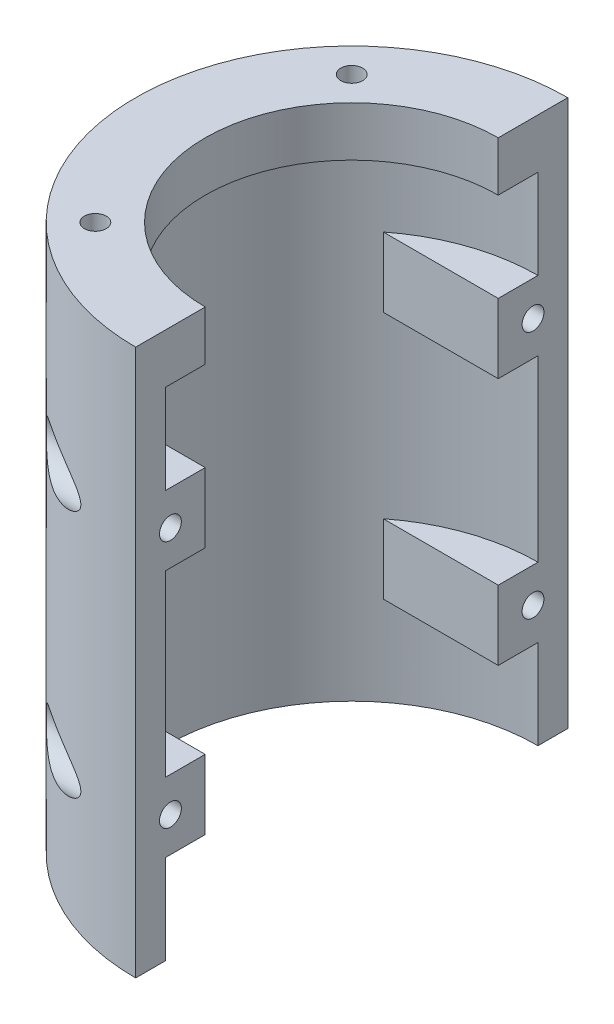
SolidWorks part; units mm, degrees
ref_plane "正面" through (0, 0, 0) normal (0, 0, 1) x (1, 0, 0)
ref_plane "平面" through (0, 0, 0) normal (0, 1, 0) x (1, 0, 0)
ref_plane "右側面" through (0, 0, 0) normal (1, 0, 0) x (0, 0, -1)
sketch "ｽｹｯﾁ1" plane through (0, 0, 0) normal (0, 1, 0) x (1, 0, 0)
  line L0 (0, -21.75) -> (0, -14.75)
  line L1 (0, -14.75) -> (0, 14.75) construction
  line L2 (0, 14.75) -> (0, 21.75)
  arc A0 (0, 21.75) -> (0, -21.75) centre (0, 0) ccw
  arc A1 (0, 14.75) -> (0, -14.75) centre (0, 0) ccw
  dimension "D1" = 14.75
  dimension "D2" = 7
extrude "ﾎﾞｽ - 押し出し1" add sketch "ｽｹｯﾁ1" along normal blind 55
sketch "ｽｹｯﾁ2" plane through (0, 55, 0) normal (0, 1, 0) x (1, 0, 0)
  circle A0 centre (0, 0) radius 14.75
  circle A1 centre (0, 0) radius 18.75
  arc A2 (0, 14.75) -> (0, -14.75) centre (0, 0) ccw construction
  arc A3 (0, 21.75) -> (0, -21.75) centre (0, 0) ccw construction
  dimension "D1" = 3
extrude "ｶｯﾄ - 押し出し1" cut sketch "ｽｹｯﾁ2" against normal through all from offset 5 offset against normal yes
sketch "ｽｹｯﾁ4" plane through (0, 0, 0) normal (1, 0, 0) x (0, 0, -1)
  line L0 (-14.75, 12.5) -> (-21.75, 12.5) construction
  line L1 (-21.75, 41) -> (-21.75, 34)
  line L2 (-18.75, 50) -> (-14.75, 50) construction
  line L3 (21.75, 55) -> (21.75, 0) construction
  line L4 (18.75, 50) -> (18.75, 0) construction
  line L5 (-21.75, 16) -> (-14.75, 16)
  line L6 (-14.75, 16) -> (-14.75, 9)
  line L7 (-14.75, 9) -> (-21.75, 9)
  line L8 (-21.75, 9) -> (-21.75, 16)
  line L9 (-21.75, 50) -> (21.75, 50) construction
  line L10 (0, 25) -> (-21.75, 25) construction
  line L11 (0, 25) -> (21.75, 25) construction
  line L12 (-21.75, 37.5) -> (21.75, 37.5) construction
  line L13 (-21.75, 0) -> (21.75, 0) construction
  line L14 (0, 50) -> (0, 0) construction
  line L15 (-18.25, 50) -> (-18.25, 0) construction
  line L16 (18.75, 50) -> (18.75, 37.5) construction
  line L17 (18.75, 37.5) -> (18.75, 25) construction
  line L18 (-21.75, 55) -> (-21.75, 0) construction
  line L19 (-21.75, 34) -> (-14.75, 34)
  line L20 (-14.75, 34) -> (-14.75, 41)
  line L21 (-14.75, 41) -> (-21.75, 41)
  line L22 (21.75, 9) -> (21.75, 16)
  line L23 (21.75, 16) -> (14.75, 16)
  line L24 (14.75, 16) -> (14.75, 9)
  line L25 (14.75, 9) -> (21.75, 9)
  line L26 (21.75, 34) -> (14.75, 34)
  line L27 (21.75, 41) -> (21.75, 34)
  line L28 (14.75, 41) -> (21.75, 41)
  line L29 (14.75, 34) -> (14.75, 41)
  circle A0 centre (-18.25, 37.5) radius 1.1 construction
  circle A1 centre (18.25, 37.5) radius 1.1 construction
  circle A2 centre (18.25, 12.5) radius 1.1 construction
  circle A3 centre (-18.25, 12.5) radius 1.1 construction
  dimension "D1" = 2.2
  dimension "D2" = 3.5
  dimension "D3" = 7
  dimension "D4" = 7
extrude "ﾎﾞｽ - 押し出し3" add sketch "ｽｹｯﾁ4" against normal up to next
sketch "ｽｹｯﾁ3" plane through (0, 0, 0) normal (1, 0, 0) x (0, 0, -1)
  line L0 (-21.75, 50) -> (21.75, 50) construction
  line L1 (0, 25) -> (-21.75, 25) construction
  line L2 (0, 25) -> (21.75, 25) construction
  line L3 (-21.75, 55) -> (-21.75, 0) construction
  line L4 (-21.75, 37.5) -> (21.75, 37.5) construction
  line L5 (21.75, 55) -> (21.75, 0) construction
  line L6 (-21.75, 0) -> (21.75, 0) construction
  line L7 (0, 50) -> (0, 0) construction
  line L8 (14.75, 50) -> (18.75, 50) construction
  line L9 (-18.25, 50) -> (-18.25, 0) construction
  line L10 (18.75, 50) -> (18.75, 37.5) construction
  line L11 (18.75, 37.5) -> (18.75, 25) construction
  line L12 (18.75, 50) -> (18.75, 41) construction
  circle A0 centre (-18.25, 37.5) radius 1.1
  circle A1 centre (18.25, 37.5) radius 1.1
  circle A2 centre (18.25, 12.5) radius 1.1
  circle A3 centre (-18.25, 12.5) radius 1.1
  dimension "D1" = 2.2
  dimension "D2" = 3.5
extrude "ｶｯﾄ - 押し出し2" cut sketch "ｽｹｯﾁ3" against normal blind 5
sketch "ｽｹｯﾁ5" plane through (0, 0, 0) normal (1, 0, 0) x (0, 0, -1)
  circle A0 centre (-18.25, 37.5) radius 2.5
  circle A1 centre (-18.25, 12.5) radius 2.5
  circle A2 centre (18.25, 12.5) radius 2.5
  circle A3 centre (18.25, 37.5) radius 2.5
  dimension "D1" = 5
extrude "ｶｯﾄ - 押し出し3" cut sketch "ｽｹｯﾁ5" against normal through all from offset 4 offset against normal yes
sketch "ｽｹｯﾁ6" plane through (0, 55, 0) normal (0, 1, 0) x (1, 0, 0)
  line L0 (0, 0) -> (-14.75, 0) construction
  line L1 (-14.75, 0) -> (-18.25, 0) construction
  line L2 (-18.25, 0) -> (-21.75, 0) construction
  line L3 (0, 0) -> (-12.9047, -12.9047) construction
  line L4 (-12.9047, 12.9047) -> (0, 0) construction
  circle A0 centre (0, 0) radius 18.25 construction
  arc A1 (0, 14.75) -> (0, -14.75) centre (0, 0) ccw construction
  arc A2 (0, 21.75) -> (0, -21.75) centre (0, 0) ccw construction
  circle A3 centre (-12.9047, -12.9047) radius 1.1
  circle A4 centre (-12.9047, 12.9047) radius 1.1
  dimension "D2" = 2.2
  dimension "D1" = 45
  dimension "D4" = 90
  dimension "D3" = 2
extrude "ｶｯﾄ - 押し出し4" cut sketch "ｽｹｯﾁ6" against normal blind 4
